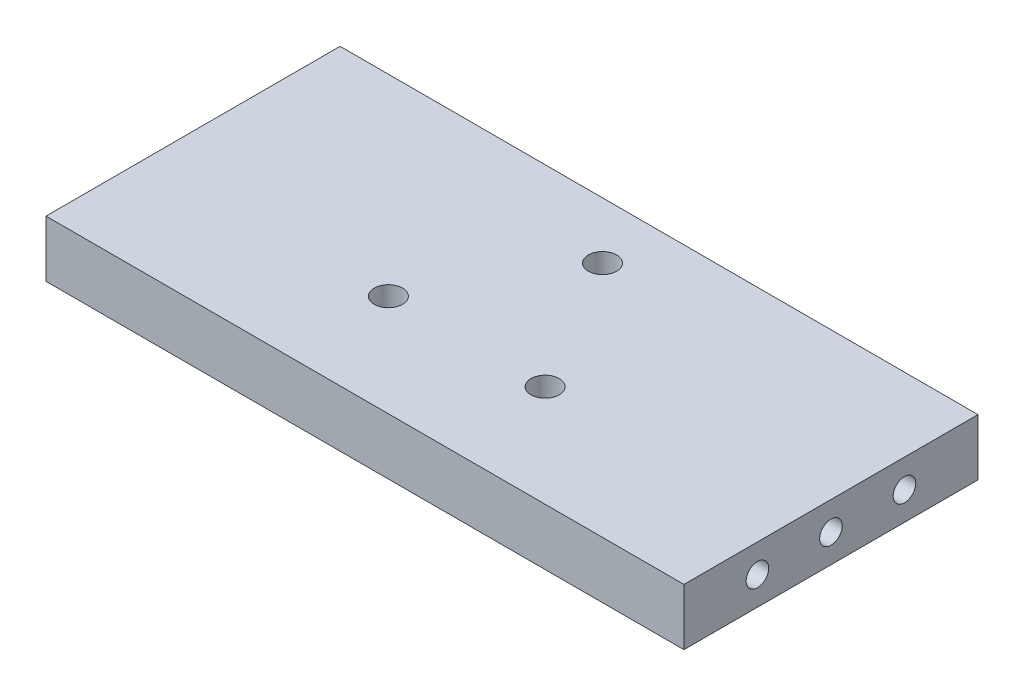
SolidWorks part; units mm, degrees
ref_plane "Front Plane" through (0, 0, 0) normal (0, 0, 1) x (1, 0, 0)
ref_plane "Top Plane" through (0, 0, 0) normal (0, 1, 0) x (1, 0, 0)
ref_plane "Right Plane" through (0, 0, 0) normal (1, 0, 0) x (0, 0, -1)
sketch "Sketch1" plane through (0, 0, 0) normal (0, 1, 0) x (1, 0, 0)
  line L1 (0, 0) -> (56.4, 0)
  line L2 (0, 0) -> (0, 26)
  line L3 (0, 26) -> (56.4, 26)
  line L4 (56.4, 0) -> (56.4, 26)
  dimension "D1" = 56.4
  dimension "D2" = 26
extrude "Boss-Extrude1" add sketch "Sketch1" along normal blind 5
sketch "Sketch2" plane through (0, 5, 0) normal (0, 1, 0) x (1, 0, 0)
  line L1 (56.4, 0) -> (56.4, 26) construction
  line L2 (0, 0) -> (56.4, 0) construction
  line L3 (21.2718, 9) -> (28.2, 21)
  line L4 (28.2, 21) -> (35.1282, 9)
  line L5 (35.1282, 9) -> (21.2718, 9)
  circle A0 centre (28.2, 13) radius 8
  point P2 (26.2826, 13)
  point P12 (0, 0)
  dimension "D1" = 28.2
  dimension "D3" = 16
  dimension "D2" = 13
sketch "Sketch5" plane through (56.4, 0, 0) normal (1, 0, 0) x (0, 0, -1)
  line L1 (0, 5) -> (0, 0) construction
  line L2 (21, 5) -> (5, 5) construction
  line L3 (9, 5) -> (21, 5) construction
  circle A0 centre (6.5, 2.5) radius 1
  circle A1 centre (13, 2.5) radius 1
  circle A2 centre (19.5, 2.5) radius 1
  point P0 (6.5, 2.5)
  point P2 (13, 2.5)
  point P4 (19.5, 2.5)
  dimension "D4" = 2
  dimension "D1" = 6.5
  dimension "D2" = 6.5
  dimension "D3" = 6.5
  dimension "D5" = 2.5
  dimension "D6" = 2.5
  dimension "D7" = 2.5
hole_wizard "Ø2.0mm Dowel Hole1" positions "Sketch5" profile "Sketch6" hole size "Ø2.0" standard "ANSI Metric"
sketch "Sketch6" plane through (56.4, 2.5, -6.5) normal (0, 1, 0) x (0, 0, -1)
  line L0 (0, 0) -> (0, 7.6009)
  line L1 (0, 7.6009) -> (1, 7)
  line L2 (1, 7) -> (1, 0)
  line L5 (1, 0) -> (0, 0)
  line L10 (0, 7.6009) -> (-1, 7) construction
  line L11 (0, -6.35) -> (0, 107.95) construction
  dimension "Hole Dia." = 2
  dimension "Hole Depth" = 7
  dimension "Drill Angle" = 118
sketch "Sketch7" plane through (0, 0, 0) normal (-1, 0, 0) x (0, 0, 1)
  line L0 (-26, 5) -> (-26, 0) construction
  line L1 (-5, 5) -> (-21, 5) construction
  line L2 (-21, 5) -> (-9, 5) construction
  circle A0 centre (-19.5, 2.5) radius 1
  circle A1 centre (-13, 2.5) radius 1
  circle A2 centre (-6.5, 2.5) radius 1
  point P0 (-19.5, 2.5)
  point P2 (-13, 2.5)
  point P4 (-6.5, 2.5)
  dimension "D3" = 2
  dimension "D1" = 6.5
  dimension "D2" = 2.5
  dimension "D4" = 6.5
  dimension "D5" = 6.5
  dimension "D6" = 2.5
  dimension "D7" = 2.5
hole_wizard "Ø2.0mm Dowel Hole2" positions "Sketch7" profile "Sketch8" hole size "Ø2.0" standard "ANSI Metric"
sketch "Sketch8" plane through (0, 2.5, -19.5) normal (0, 1, 0) x (0, 0, 1)
  line L0 (0, 0) -> (0, 7.6009)
  line L1 (0, 7.6009) -> (1, 7)
  line L2 (1, 7) -> (1, 0)
  line L5 (1, 0) -> (0, 0)
  line L10 (0, 7.6009) -> (-1, 7) construction
  line L11 (0, -6.35) -> (0, 107.95) construction
  dimension "Hole Dia." = 2
  dimension "Hole Depth" = 7
  dimension "Drill Angle" = 118
hole_wizard "Ø2.5mm Dowel Hole1" positions "3DSketch1" profile "Sketch9" hole size "Ø2.5" standard "ANSI Metric"
sketch3d "3DSketch1"
  point P0 (21.2718, 5, -9)
  point P3 (28.2, 5, -21)
  point P6 (35.1282, 5, -9)
sketch "Sketch9" plane through (21.2718, 5, -9) normal (1, 0, 0) x (0, 0, 1)
  line L0 (0, 0) -> (0, 8.7511)
  line L1 (0, 8.7511) -> (1.25, 8)
  line L2 (1.25, 8) -> (1.25, 0)
  line L5 (1.25, 0) -> (0, 0)
  line L10 (0, 8.7511) -> (-1.25, 8) construction
  line L11 (0, -6.35) -> (0, 107.95) construction
  dimension "Hole Dia." = 2.5
  dimension "Hole Depth" = 8
  dimension "Drill Angle" = 118
